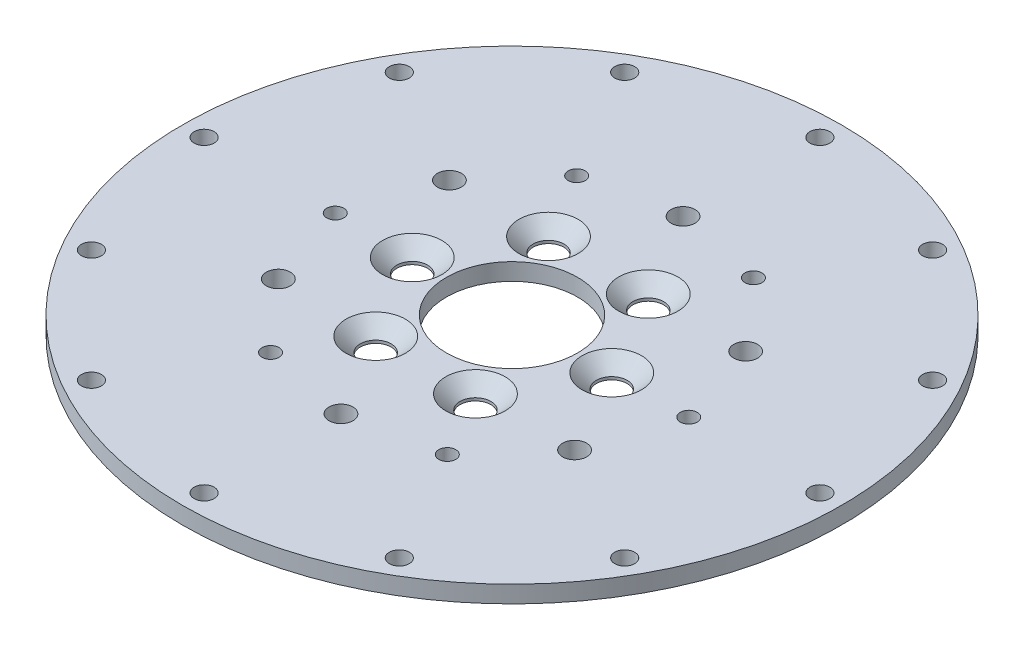
SolidWorks part; units mm, degrees
material "A-玻璃纤维"
ref_plane "前视基准面" through (0, 0, 0) normal (0, 0, 1) x (1, 0, 0)
ref_plane "上视基准面" through (0, 0, 0) normal (0, 1, 0) x (1, 0, 0)
ref_plane "右视基准面" through (0, 0, 0) normal (1, 0, 0) x (0, 0, -1)
other "Configuration Table"
sketch "草图1" plane through (0, 0, 0) normal (0, 1, 0) x (1, 0, 0)
  circle A0 centre (0, 0) radius 57.8
  dimension "D1" = 115.6
extrude "凸台-拉伸1" add sketch "草图1" along normal blind 3
sketch "草图2" plane through (0, 0, 0) normal (0, -1, 0) x (1, 0, 0)
  circle A0 centre (0, 0) radius 54 construction
  circle A1 centre (0, 54) radius 1.75
  dimension "D1" = 108
  dimension "D2" = 3.5
extrude "切除-拉伸1" cut sketch "草图2" against normal through all both
pattern_circular "阵列(圆周)1" count 12 over 360 about axis through (0, 0, 0) along (0, 1, 0) of "切除-拉伸1"
sketch "草图3" plane through (0, 0, 0) normal (0, -1, 0) x (1, 0, 0)
  circle A0 centre (0, 0) radius 30 construction
  circle A1 centre (0, 30) radius 2.1
  dimension "D1" = 60
  dimension "D2" = 4.2
extrude "切除-拉伸2" cut sketch "草图3" against normal through all both
pattern_circular "阵列(圆周)2" count 6 over 360 about axis through (0, 0, 0) along (0, 1, 0) of "切除-拉伸2"
sketch "草图4" plane through (0, 0, 0) normal (0, -1, 0) x (1, 0, 0)
  circle A0 centre (0, 0) radius 31 construction
  circle A1 centre (31, 0) radius 1.49
  dimension "D1" = 62
  dimension "D2" = 2.98
extrude "切除-拉伸3" cut sketch "草图4" against normal through all both
pattern_circular "阵列(圆周)3" count 6 over 360 about axis through (0, 0, 0) along (0, 1, 0) of "切除-拉伸3"
sketch "草图5" plane through (0, 3, 0) normal (0, 1, 0) x (1, 0, 0)
  circle A0 centre (0, 0) radius 17.5 construction
  circle A1 centre (17.5, 0) radius 2.7
  circle A2 centre (0, 0) radius 11.5
  dimension "D1" = 35
  dimension "D2" = 5.4
  dimension "D3" = 23
extrude "切除-拉伸4" cut sketch "草图5" against normal through all both
pattern_circular "阵列(圆周)4" count 6 over 360 about axis through (0, 0, 0) along (0, 1, 0) of "切除-拉伸4"
chamfer "倒角1" distance 2.5 angle 45 6 edges at (-11.0883, 3, 13.8054) (-17.5, 3, -2.7) (-6.4117, 3, -16.5054) (11.0883, 3, -13.8054) (17.5, 3, 2.7) (6.4117, 3, 16.5054)
